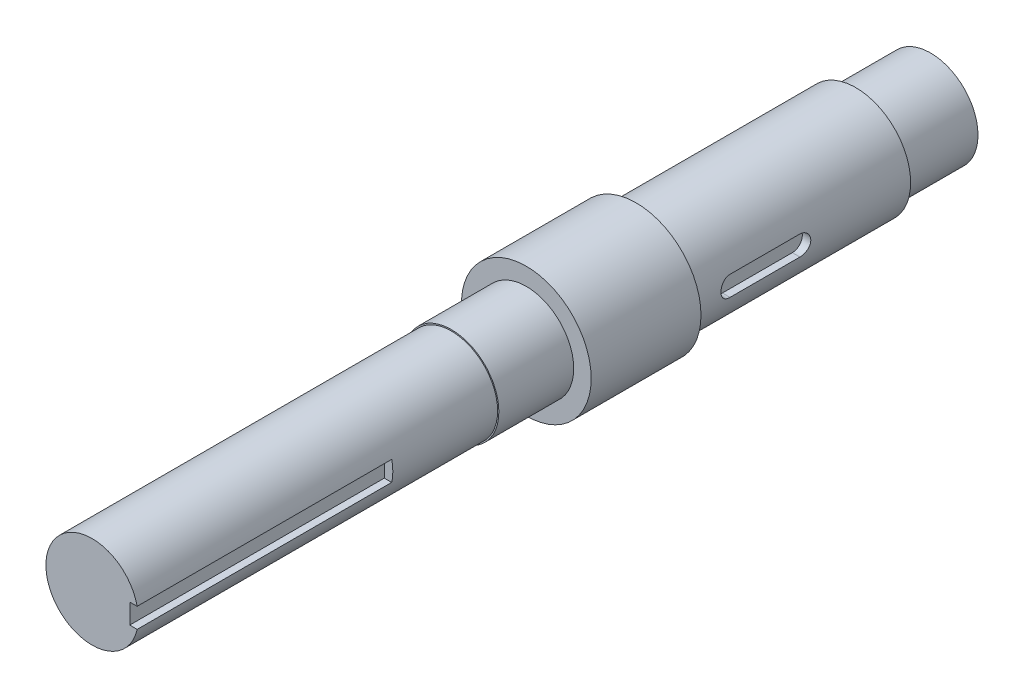
SolidWorks part; units mm, degrees
ref_plane "Front Plane" through (0, 0, 0) normal (0, 0, 1) x (1, 0, 0)
ref_plane "Top Plane" through (0, 0, 0) normal (0, 1, 0) x (1, 0, 0)
ref_plane "Right Plane" through (0, 0, 0) normal (1, 0, 0) x (0, 0, -1)
sketch "Sketch2" plane through (0, 0, 0) normal (0, 1, 0) x (1, 0, 0)
  line L0 (0, 0) -> (0, 168) construction
  line L1 (0, 0) -> (-9.25, 0)
  line L2 (-9.25, 0) -> (-9.25, 72)
  line L3 (-9.25, 72) -> (-9.5, 72)
  line L4 (-9.5, 72) -> (-9.5, 87)
  line L5 (-9.5, 87) -> (-13, 87)
  line L6 (-13, 87) -> (-13, 109)
  line L7 (-13, 109) -> (-11, 109)
  line L8 (-11, 109) -> (-11, 153)
  line L9 (-11, 153) -> (-9.5, 153)
  line L10 (-9.5, 153) -> (-9.5, 168)
  line L11 (-9.5, 168) -> (0, 168)
  line L12 (0, 0) -> (0, 168)
  point P13 (0, 56.2579)
  point P15 (0, -28.8351)
  point P16 (0, 52.8939)
  point P17 (0, 50.551)
  point P18 (0, 48.416)
  point P19 (-17.9559, 18.0069)
  point P20 (0, 0)
  point P21 (0, 0)
  point P22 (0, 168.4725)
  dimension "D1" = 9.5
  dimension "D2" = 15
  dimension "D3" = 11
  dimension "D4" = 13
  dimension "D5" = 9.25
  dimension "D6" = 9.5
  dimension "D7" = 15
  dimension "D8" = 168
  dimension "D9" = 72
  dimension "D10" = 44
revolve "Revolve1" add sketch "Sketch2" angle 360 about L0
sketch "Sketch3" plane through (0, 0, 0) normal (0, 0, 1) x (1, 0, 0)
  line L1 (7.55, 2) -> (11.6297, 2)
  line L2 (7.55, 2) -> (7.55, -2)
  line L3 (7.55, -2) -> (11.6297, -2)
  line L4 (11.6297, 2) -> (11.6297, -2)
  circle A0 centre (0, 0) radius 9.25 construction
  circle A1 centre (0, 0) radius 9.25 construction
  point P4 (7.55, 0)
  point P5 (0, 0)
  point P6 (-9.25, 0)
  point P12 (-9.25, 0)
  dimension "D1" = 4
  dimension "D2" = 16.8
extrude "Cut-Extrude1" cut sketch "Sketch3" against normal blind 51
sketch "Sketch4" plane through (0, 0, 0) normal (1, 0, 0) x (0, 0, -1)
  line L0 (109, -11) -> (109, 11) construction
  line L1 (117, 2) -> (131, 2)
  line L2 (117, 2) -> (117, -2) construction
  line L3 (117, -2) -> (131, -2)
  line L4 (131, 2) -> (131, -2) construction
  line L5 (117, 2) -> (131, -2) construction
  line L6 (117, -2) -> (131, 2) construction
  line L7 (109, -13) -> (109, 13) construction
  arc A0 (117, -2) -> (117, 2) centre (117, 0) cw
  arc A1 (131, -2) -> (131, 2) centre (131, 0) ccw
  point P0 (124, 0)
  point P13 (109, 0)
  dimension "D1" = 8
  dimension "D2" = 4
  dimension "D3" = 14
extrude "Cut-Extrude2" cut sketch "Sketch4" against normal blind 1.7 from offset 11
